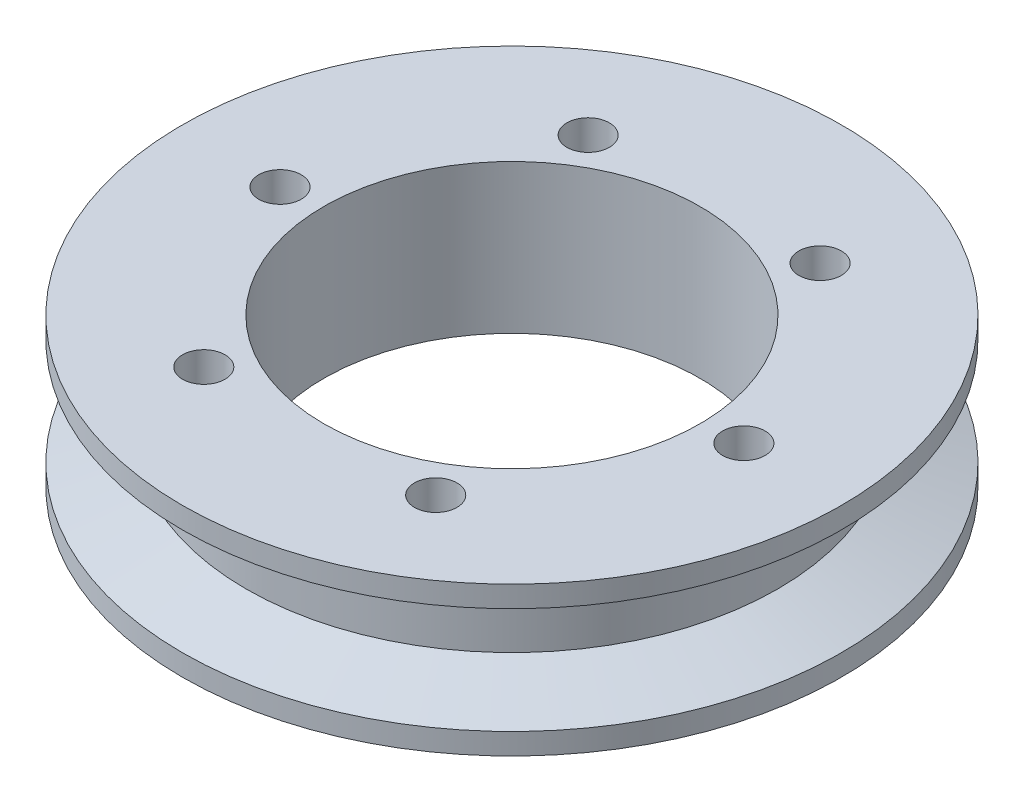
SolidWorks part; units mm, degrees
ref_plane "Front Plane" through (0, 0, 0) normal (0, 0, 1) x (1, 0, 0)
ref_plane "Top Plane" through (0, 0, 0) normal (0, 1, 0) x (1, 0, 0)
ref_plane "Right Plane" through (0, 0, 0) normal (1, 0, 0) x (0, 0, -1)
sketch "Sketch1" plane through (0, 0, 0) normal (0, 0, 1) x (1, 0, 0)
  line L0 (0, 20.733) -> (0, -20.0076) construction
  line L1 (-17.7, 8.1757) -> (-17.7, -5.8243)
  line L2 (-17.7, 1.1757) -> (-33.1595, 1.1757) construction
  line L3 (-25, -1.6393) -> (-25, 3.9907)
  line L5 (-31, 6.1757) -> (-25, 3.9907)
  line L6 (-25, -1.6393) -> (-31, -3.8243)
  line L7 (-31, 6.1757) -> (-31, 8.1757)
  line L8 (-31, 8.1757) -> (-17.7, 8.1757)
  line L9 (-17.7, -5.8243) -> (-31, -5.8243)
  line L10 (-31, -5.8243) -> (-31, -3.8243)
  point P10 (-25, 1.1757)
  point P13 (-31, 1.1757)
  dimension "D1" = 14
  dimension "D2" = 17.7
  dimension "D3" = 7.3
  dimension "D4" = 5.63
  dimension "D5" = 10
revolve "Revolve1" add sketch "Sketch1" angle 360 about L0
sketch "Sketch2" plane through (0, 8.1757, 0) normal (0, 1, 0) x (1, 0, 0)
  circle A0 centre (11.0812, -18.2491) radius 2
  circle A1 centre (0, 0) radius 17.7 construction
  circle A2 centre (-10.2636, -18.7211) radius 2
  circle A3 centre (-21.3448, -0.472) radius 2
  circle A4 centre (-11.0812, 18.2491) radius 2
  circle A5 centre (10.2636, 18.7211) radius 2
  circle A6 centre (21.3448, 0.472) radius 2
  point P16 (0, 0)
  dimension "D1" = 21.35
  dimension "D2" = 6
extrude "Cut-Extrude1" cut sketch "Sketch2" against normal blind 14
